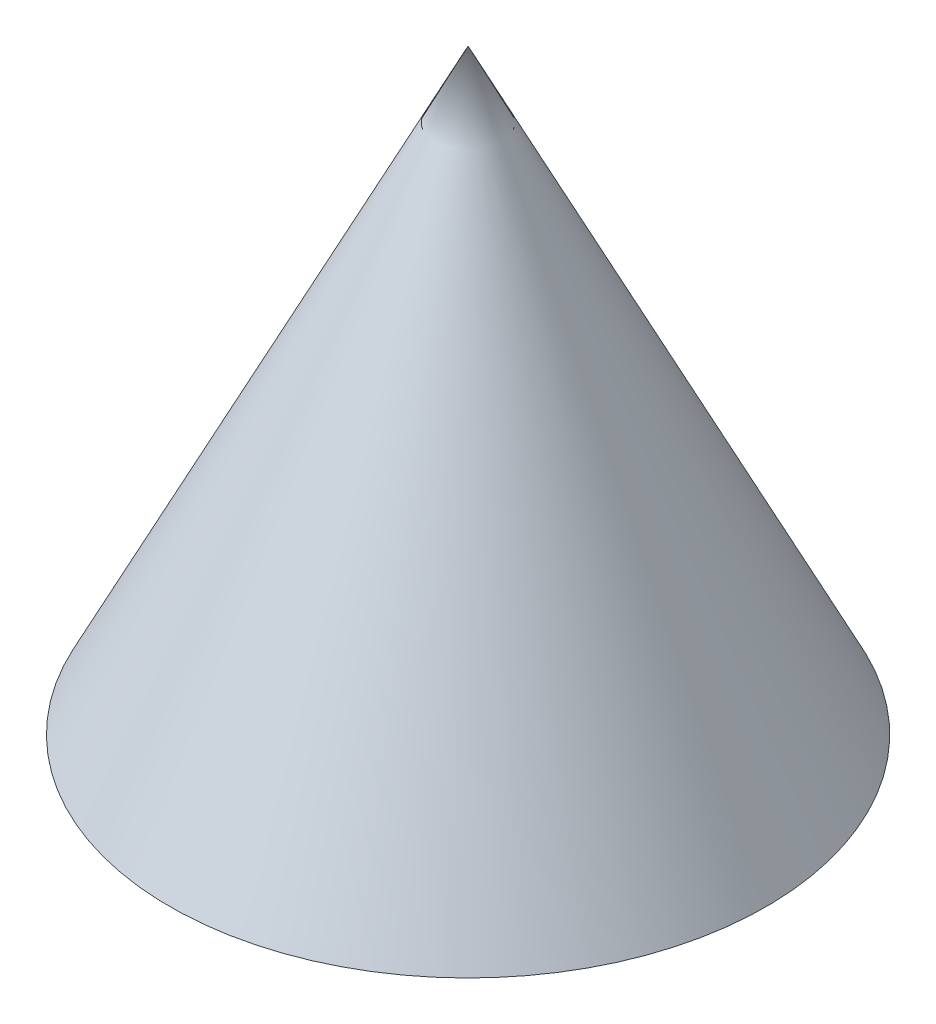
SolidWorks part; units mm, degrees
ref_plane "前视基准面" through (0, 0, 0) normal (0, 0, 1) x (1, 0, 0)
ref_plane "上视基准面" through (0, 0, 0) normal (0, 1, 0) x (1, 0, 0)
ref_plane "右视基准面" through (0, 0, 0) normal (1, 0, 0) x (0, 0, -1)
other "Configuration Table"
sketch "草图1" plane through (0, 0, 0) normal (0, 0, 1) x (1, 0, 0)
  line L0 (0, 0) -> (0, 200) construction
  line L1 (0, 0) -> (100, 0)
  line L2 (100, 0) -> (0, 200)
  line L3 (0, 200) -> (0, 0)
revolve "旋转1" add sketch "草图1" angle 360 about L0
